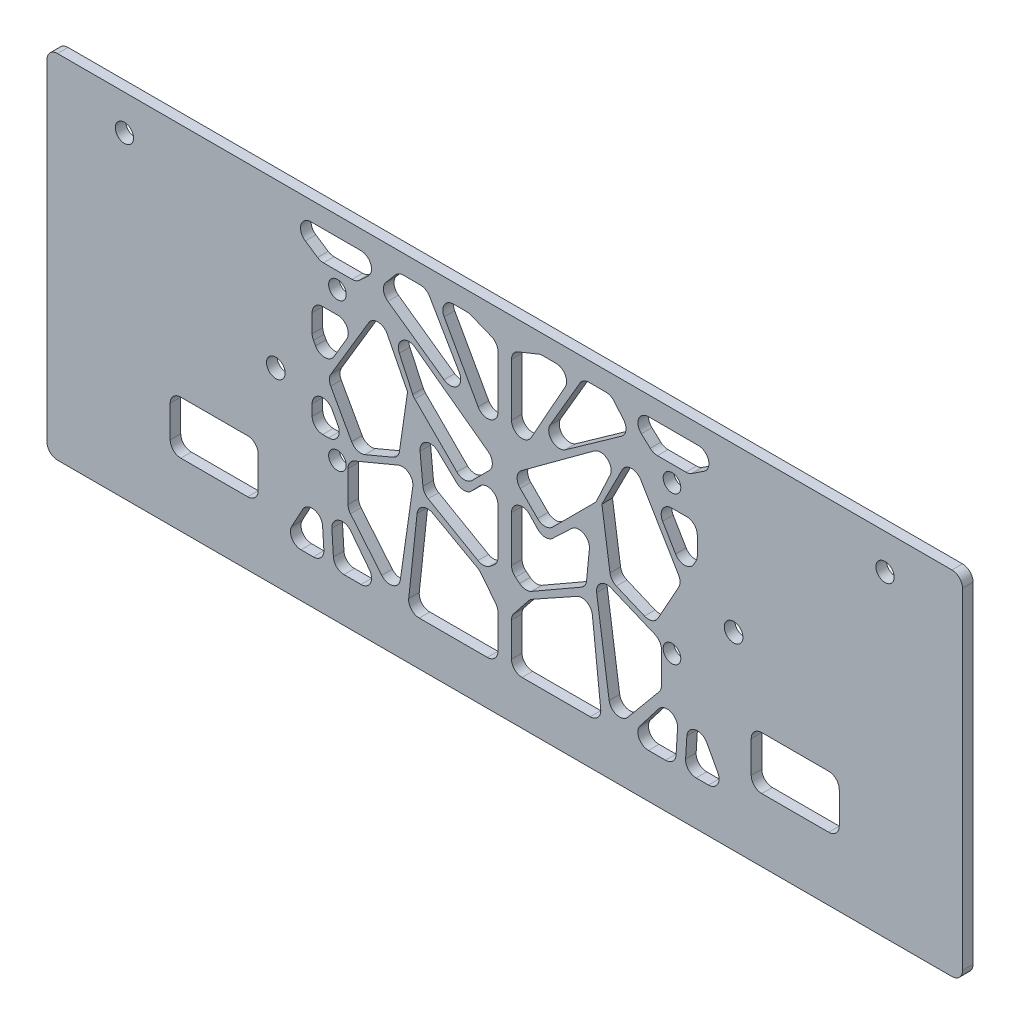
SolidWorks part; units mm, degrees
material "Thornel Mat VMA"
ref_plane "前视基准面" through (0, 0, 0) normal (0, 0, 1) x (1, 0, 0)
ref_plane "上视基准面" through (0, 0, 0) normal (0, 1, 0) x (1, 0, 0)
ref_plane "右视基准面" through (0, 0, 0) normal (1, 0, 0) x (0, 0, -1)
other "Configuration Table"
sketch "草图1" plane through (0, 0, 0) normal (0, 0, 1) x (1, 0, 0)
  line L1 (130, -50) -> (-130, -50)
  line L2 (130, -50) -> (130, 50)
  line L3 (130, 50) -> (-130, 50)
  line L4 (-130, -50) -> (-130, 50)
  line L5 (130, -50) -> (-130, 50) construction
  line L6 (130, 50) -> (-130, -50) construction
  point P0 (0, 0)
  dimension "D1" = 260
  dimension "D2" = 100
extrude "凸台-拉伸1" add sketch "草图1" along normal blind 3
fillet "圆角1" radius 3 4 edges at (130, 50, 1.5) (130, -50, 1.5) (-130, -50, 1.5) (-130, 50, 1.5)
sketch "草图3" plane through (0, 0, 0) normal (0, 0, -1) x (-1, 0, 0)
  line L0 (0, 50) -> (0, -50) construction
  line L1 (-127, 50) -> (127, 50) construction
  line L2 (127, -50) -> (-127, -50) construction
  line L3 (47.5, 50) -> (47.5, -50) construction
  line L5 (-47.5, 50) -> (-47.5, -50) construction
  line L6 (-130, -47) -> (-130, 47) construction
  circle A0 centre (47.5, 31.7) radius 2.5
  circle A1 centre (47.5, -10.3) radius 2.5
  circle A2 centre (-47.5, -10.3) radius 2.5
  circle A3 centre (-47.5, 31.7) radius 2.5
  circle A4 centre (-65, 3.7) radius 2.65
  circle A5 centre (65, 3.7) radius 2.65
  dimension "D1" = 5
  dimension "D3" = 42
  dimension "D4" = 18.3
  dimension "D5" = 5.3
  dimension "D6" = 46.3
  dimension "D7" = 65
  dimension "D2" = 47.5
extrude "切除-拉伸1" cut sketch "草图3" against normal blind 3
sketch "草图4" plane through (0, 0, 0) normal (0, 0, -1) x (-1, 0, 0)
  line L0 (-130, -17) -> (130, -17) construction
  line L1 (-130, -47) -> (-130, 47) construction
  line L2 (130, 47) -> (130, -47) construction
  line L3 (0, 50) -> (0, -50) construction
  line L4 (-127, 50) -> (127, 50) construction
  line L5 (127, -50) -> (-127, -50) construction
  line L6 (70, -17) -> (70, -32)
  line L7 (-95, -17) -> (-70, -17)
  line L8 (-95, -17) -> (-95, -32)
  line L9 (-95, -32) -> (-70, -32)
  line L10 (-70, -17) -> (-70, -32)
  line L11 (95, -32) -> (70, -32)
  line L12 (95, -17) -> (95, -32)
  line L13 (95, -17) -> (70, -17)
  dimension "D1" = 67
  dimension "D2" = 25
  dimension "D3" = 15
  dimension "D4" = 70
extrude "切除-拉伸2" cut sketch "草图4" against normal blind 3
fillet "圆角2" radius 3 8 edges at (-95, -17, 1.5) (-95, -32, 1.5) (-70, -32, 1.5) (-70, -17, 1.5) (70, -17, 1.5) (70, -32, 1.5) (95, -32, 1.5) (95, -17, 1.5)
sketch "草图5" plane through (0, 0, 0) normal (0, 0, -1) x (-1, 0, 0)
  line L0 (0, 50) -> (0, -50) construction
  line L1 (-127, 50) -> (127, 50) construction
  line L2 (127, -50) -> (-127, -50) construction
  line L3 (-130, -47) -> (-130, 47) construction
  circle A0 centre (-108, 40) radius 2.6
  circle A1 centre (108, 40) radius 2.6
  dimension "D1" = 5.2
  dimension "D2" = 22
  dimension "D3" = 10
extrude "切除-拉伸3" cut sketch "草图5" against normal blind 10
sketch "草图6" plane through (0, 0, 0) normal (0, 0, -1) x (-1, 0, 0)
  line L0 (-1.9245, 39.2502) -> (1.9245, 39.2502) construction
  line L1 (0, 39.2502) -> (0, -50.9783) construction
  line L2 (-1.9245, -24.8225) -> (1.9245, -24.8225) construction
  point P7 (0, -24.8225)
  line B0 (-38.4364, -32.6363) -> (-43.7127, -25.8023)
  line B1 (-45.6595, -37.4697) -> (-40.8111, -37.4697)
  line B2 (-49.0815, -27.8231) -> (-48.6537, -34.6571)
  line B3 (-51.3608, -34.2822) -> (-51.7232, -28.4933)
  line B4 (-57.8516, -37.4697) -> (-54.3549, -37.4697)
  line B5 (-57.3555, -27.2524) -> (-60.4897, -33.0413)
  line B6 (13.5751, 3.8156) -> (25.5304, 15.7709)
  line B7 (4.3957, 8.7524) -> (9.3325, 3.8156)
  line B8 (25.4376, 28.4877) -> (4.7415, 13.2919)
  line B9 (26.1292, 16.6269) -> (29.9332, 24.8041)
  line B10 (9.3893, 1.2104) -> (7.1012, 3.6228)
  line B11 (18.9944, 6.1855) -> (13.6305, 1.0981)
  line B12 (23.2357, -4.5515) -> (24.0446, 3.7166)
  line B13 (7.5961, -14.9727) -> (21.7421, -6.862)
  line B14 (3.0494, -13.7675) -> (4.2288, -14.7119)
  line B15 (1.9245, 1.5584) -> (1.9245, -11.4257)
  line B16 (27.2608, -34.1487) -> (24.886, -12.0769)
  line B17 (4.9245, -37.4697) -> (24.278, -37.4697)
  line B18 (1.9245, -24.8225) -> (1.9245, -34.4697)
  line B19 (6.876, -17.5858) -> (2.5828, -22.9473)
  line B20 (20.4438, -9.7768) -> (7.7583, -16.8399)
  line B21 (-1.9245, -34.4697) -> (-1.9245, -24.8225)
  line B22 (-24.278, -37.4697) -> (-4.9245, -37.4697)
  line B23 (-24.886, -12.0769) -> (-27.2608, -34.1487)
  line B24 (-7.7583, -16.8399) -> (-20.4438, -9.7768)
  line B25 (-2.5828, -22.9473) -> (-6.876, -17.5858)
  line B26 (-29.6511, -30.7817) -> (-26.1014, -6.0365)
  line B27 (-43.8095, -21.5832) -> (-34.9282, -32.2728)
  line B28 (-44.502, -10.805) -> (-44.502, -19.6661)
  line B29 (-30.2276, -2.8425) -> (-42.6586, -8.0369)
  line B30 (-13.6305, 1.0981) -> (-18.9944, 6.1855)
  line B31 (-7.1012, 3.6228) -> (-9.3893, 1.2104)
  line B32 (-1.9245, -11.4257) -> (-1.9245, 1.5584)
  line B33 (-4.2288, -14.7119) -> (-3.0494, -13.7675)
  line B34 (-21.7421, -6.862) -> (-7.5961, -14.9727)
  line B35 (-24.0446, 3.7166) -> (-23.2357, -4.5515)
  line B36 (-4.7415, 13.2919) -> (-25.4376, 28.4877)
  line B37 (-9.3325, 3.8156) -> (-4.3957, 8.7524)
  line B38 (-25.5304, 15.7709) -> (-13.5751, 3.8156)
  line B39 (-29.9332, 24.8041) -> (-26.1292, 16.6269)
  line B40 (-29.8981, 0.7081) -> (-27.5954, 16.4873)
  line B41 (-39.6959, -4.9911) -> (-31.702, -1.6233)
  line B42 (-49.4076, 6.9859) -> (-43.4834, -3.6828)
  line B43 (-38.62, 28.0131) -> (-49.3623, 9.9775)
  line B44 (-27.5954, 16.4873) -> (-33.3685, 27.8379)
  line B45 (-54.3064, 15.808) -> (-53.7196, 14.7513)
  line B46 (-54.6836, 22.4337) -> (-54.6836, 17.2643)
  line B47 (-47.4272, 25.4337) -> (-51.6836, 25.4337)
  line B48 (-48.5124, 14.6844) -> (-44.8427, 20.9104)
  line B49 (-40.8365, 44.6049) -> (-54.9861, 44.6049)
  line B50 (-41.3149, 37.0828) -> (-38.8028, 39.3995)
  line B51 (-51.4759, 36.2882) -> (-43.3487, 36.2882)
  line B52 (-56.6386, 39.101) -> (-53.1283, 36.7843)
  line B53 (-12.9018, 28.6255) -> (-21.3518, 43.1161)
  line B54 (-33.1725, 35.9785) -> (-17.2293, 24.6675)
  line B55 (-31.0413, 43.5411) -> (-33.7281, 40.3615)
  line B56 (-23.9433, 44.6049) -> (-28.7499, 44.6049)
  line B57 (-17.1953, 40.1446) -> (-7.5451, 22.8267)
  line B58 (-10.751, 44.6049) -> (-14.5747, 44.6049)
  line B59 (-3.8005, 42.0317) -> (-9.6269, 44.3863)
  line B60 (-1.9245, 24.287) -> (-1.9245, 39.2502)
  line B61 (9.6269, 44.3863) -> (3.8005, 42.0317)
  line B62 (14.5747, 44.6049) -> (10.751, 44.6049)
  line B63 (7.5451, 22.8267) -> (17.1953, 40.1446)
  line B64 (1.9245, 39.2502) -> (1.9245, 24.287)
  line B65 (17.2293, 24.6675) -> (33.1725, 35.9785)
  line B66 (21.3518, 43.1161) -> (12.9018, 28.6255)
  line B67 (28.7499, 44.6049) -> (23.9433, 44.6049)
  line B68 (33.7281, 40.3615) -> (31.0413, 43.5411)
  line B69 (43.3487, 36.2882) -> (51.4759, 36.2882)
  line B70 (38.8028, 39.3995) -> (41.3149, 37.0828)
  line B71 (54.9861, 44.6049) -> (40.8365, 44.6049)
  line B72 (53.1283, 36.7843) -> (56.6386, 39.101)
  line B73 (51.6836, 25.4337) -> (47.4272, 25.4337)
  line B74 (54.6836, 17.2643) -> (54.6836, 22.4337)
  line B75 (53.7196, 14.7513) -> (54.3064, 15.808)
  line B76 (44.8427, 20.9104) -> (48.5124, 14.6844)
  line B77 (49.0523, 1.4853) -> (47.3653, -1.5951)
  line B78 (54.6836, -3.0361) -> (54.6836, 0.0443)
  line B79 (49.9966, -6.0361) -> (51.6836, -6.0361)
  line B80 (43.4834, -3.6828) -> (49.4076, 6.9859)
  line B81 (31.702, -1.6233) -> (39.6959, -4.9911)
  line B82 (27.5954, 16.4873) -> (29.8981, 0.7081)
  line B83 (33.3685, 27.8379) -> (27.5954, 16.4873)
  line B84 (49.3623, 9.9775) -> (38.62, 28.0131)
  line B85 (60.4897, -33.0413) -> (57.3555, -27.2524)
  line B86 (54.3549, -37.4697) -> (57.8516, -37.4697)
  line B87 (51.7232, -28.4933) -> (51.3608, -34.2822)
  line B88 (48.6537, -34.6571) -> (49.0815, -27.8231)
  line B89 (40.8111, -37.4697) -> (45.6595, -37.4697)
  line B90 (43.7127, -25.8023) -> (38.4364, -32.6363)
  line B91 (44.502, -19.6661) -> (44.502, -10.805)
  line B92 (34.9282, -32.2728) -> (43.8095, -21.5832)
  line B93 (26.1014, -6.0365) -> (29.6511, -30.7817)
  line B94 (42.6586, -8.0369) -> (30.2276, -2.8425)
  arc B95 (-40.8111, -37.4697) -> (-38.4364, -32.6363) centre (-40.8111, -34.4697) ccw
  arc B96 (-48.6537, -34.6571) -> (-45.6595, -37.4697) centre (-45.6595, -34.4697) ccw
  arc B97 (-43.7127, -25.8023) -> (-49.0815, -27.8231) centre (-46.0874, -27.6356) ccw
  arc B98 (-54.3549, -37.4697) -> (-51.3608, -34.2822) centre (-54.3549, -34.4697) ccw
  arc B99 (-60.4897, -33.0413) -> (-57.8516, -37.4697) centre (-57.8516, -34.4697) ccw
  arc B100 (-51.7232, -28.4933) -> (-57.3555, -27.2524) centre (-54.7173, -28.6808) ccw
  arc B101 (9.3325, 3.8156) -> (13.5751, 3.8156) centre (11.4538, 5.937) ccw
  arc B102 (4.7415, 13.2919) -> (4.3957, 8.7524) centre (6.517, 10.8737) ccw
  arc B103 (29.9332, 24.8041) -> (25.4376, 28.4877) centre (27.2131, 26.0695) ccw
  arc B104 (25.5304, 15.7709) -> (26.1292, 16.6269) centre (23.4091, 17.8923) ccw
  arc B105 (9.3893, 1.2104) -> (13.6305, 1.0981) centre (11.566, 3.2748) ccw
  arc B106 (24.0446, 3.7166) -> (18.9944, 6.1855) centre (21.0588, 4.0088) ccw
  arc B107 (21.7421, -6.862) -> (23.2357, -4.5515) centre (20.2499, -4.2594) ccw
  arc B108 (4.2288, -14.7119) -> (7.5961, -14.9727) centre (6.1039, -12.3701) ccw
  arc B109 (1.9245, -11.4257) -> (3.0494, -13.7675) centre (4.9245, -11.4257) ccw
  arc B110 (7.1012, 3.6228) -> (1.9245, 1.5584) centre (4.9245, 1.5584) ccw
  arc B111 (24.278, -37.4697) -> (27.2608, -34.1487) centre (24.278, -34.4697) ccw
  arc B112 (1.9245, -34.4697) -> (4.9245, -37.4697) centre (4.9245, -34.4697) ccw
  arc B113 (2.5828, -22.9473) -> (1.9245, -24.8225) centre (4.9245, -24.8225) ccw
  arc B114 (7.7583, -16.8399) -> (6.876, -17.5858) centre (9.2177, -19.461) ccw
  arc B115 (24.886, -12.0769) -> (20.4438, -9.7768) centre (21.9032, -12.3979) ccw
  arc B116 (-4.9245, -37.4697) -> (-1.9245, -34.4697) centre (-4.9245, -34.4697) ccw
  arc B117 (-27.2608, -34.1487) -> (-24.278, -37.4697) centre (-24.278, -34.4697) ccw
  arc B118 (-20.4438, -9.7768) -> (-24.886, -12.0769) centre (-21.9032, -12.3979) ccw
  arc B119 (-6.876, -17.5858) -> (-7.7583, -16.8399) centre (-9.2177, -19.461) ccw
  arc B120 (-1.9245, -24.8225) -> (-2.5828, -22.9473) centre (-4.9245, -24.8225) ccw
  arc B121 (-34.9282, -32.2728) -> (-29.6511, -30.7817) centre (-32.6207, -30.3557) ccw
  arc B122 (-44.502, -19.6661) -> (-43.8095, -21.5832) centre (-41.502, -19.6661) ccw
  arc B123 (-42.6586, -8.0369) -> (-44.502, -10.805) centre (-41.502, -10.805) ccw
  arc B124 (-26.1014, -6.0365) -> (-30.2276, -2.8425) centre (-29.071, -5.6105) ccw
  arc B125 (-13.6305, 1.0981) -> (-9.3893, 1.2104) centre (-11.566, 3.2748) ccw
  arc B126 (-1.9245, 1.5584) -> (-7.1012, 3.6228) centre (-4.9245, 1.5584) ccw
  arc B127 (-3.0494, -13.7675) -> (-1.9245, -11.4257) centre (-4.9245, -11.4257) ccw
  arc B128 (-7.5961, -14.9727) -> (-4.2288, -14.7119) centre (-6.1039, -12.3701) ccw
  arc B129 (-23.2357, -4.5515) -> (-21.7421, -6.862) centre (-20.2499, -4.2594) ccw
  arc B130 (-18.9944, 6.1855) -> (-24.0446, 3.7166) centre (-21.0588, 4.0088) ccw
  arc B131 (-4.3957, 8.7524) -> (-4.7415, 13.2919) centre (-6.517, 10.8737) ccw
  arc B132 (-13.5751, 3.8156) -> (-9.3325, 3.8156) centre (-11.4538, 5.937) ccw
  arc B133 (-26.1292, 16.6269) -> (-25.5304, 15.7709) centre (-23.4091, 17.8923) ccw
  arc B134 (-25.4376, 28.4877) -> (-29.9332, 24.8041) centre (-27.2131, 26.0695) ccw
  arc B135 (-31.702, -1.6233) -> (-29.8981, 0.7081) centre (-32.8667, 1.1414) ccw
  arc B136 (-43.4834, -3.6828) -> (-39.6959, -4.9911) centre (-40.8606, -2.2264) ccw
  arc B137 (-49.3623, 9.9775) -> (-49.4076, 6.9859) centre (-46.7848, 8.4423) ccw
  arc B138 (-33.3685, 27.8379) -> (-38.62, 28.0131) centre (-36.0425, 26.4779) ccw
  arc B139 (-54.6836, 17.2643) -> (-54.3064, 15.808) centre (-51.6836, 17.2643) ccw
  arc B140 (-51.6836, 25.4337) -> (-54.6836, 22.4337) centre (-51.6836, 22.4337) ccw
  arc B141 (-44.8427, 20.9104) -> (-47.4272, 25.4337) centre (-47.4272, 22.4337) ccw
  arc B142 (-53.7196, 14.7513) -> (-48.5124, 14.6844) centre (-51.0968, 16.2077) ccw
  arc B143 (-38.8028, 39.3995) -> (-40.8365, 44.6049) centre (-40.8365, 41.6049) ccw
  arc B144 (-43.3487, 36.2882) -> (-41.3149, 37.0828) centre (-43.3487, 39.2882) ccw
  arc B145 (-53.1283, 36.7843) -> (-51.4759, 36.2882) centre (-51.4759, 39.2882) ccw
  arc B146 (-54.9861, 44.6049) -> (-56.6386, 39.101) centre (-54.9861, 41.6049) ccw
  arc B147 (-17.2293, 24.6675) -> (-12.9018, 28.6255) centre (-15.4934, 27.1143) ccw
  arc B148 (-33.7281, 40.3615) -> (-33.1725, 35.9785) centre (-31.4367, 38.4253) ccw
  arc B149 (-28.7499, 44.6049) -> (-31.0413, 43.5411) centre (-28.7499, 41.6049) ccw
  arc B150 (-21.3518, 43.1161) -> (-23.9433, 44.6049) centre (-23.9433, 41.6049) ccw
  arc B151 (-14.5747, 44.6049) -> (-17.1953, 40.1446) centre (-14.5747, 41.6049) ccw
  arc B152 (-9.6269, 44.3863) -> (-10.751, 44.6049) centre (-10.751, 41.6049) ccw
  arc B153 (-1.9245, 39.2502) -> (-3.8005, 42.0317) centre (-4.9245, 39.2502) ccw
  arc B154 (-7.5451, 22.8267) -> (-1.9245, 24.287) centre (-4.9245, 24.287) ccw
  arc B155 (10.751, 44.6049) -> (9.6269, 44.3863) centre (10.751, 41.6049) ccw
  arc B156 (17.1953, 40.1446) -> (14.5747, 44.6049) centre (14.5747, 41.6049) ccw
  arc B157 (1.9245, 24.287) -> (7.5451, 22.8267) centre (4.9245, 24.287) ccw
  arc B158 (3.8005, 42.0317) -> (1.9245, 39.2502) centre (4.9245, 39.2502) ccw
  arc B159 (12.9018, 28.6255) -> (17.2293, 24.6675) centre (15.4934, 27.1143) ccw
  arc B160 (23.9433, 44.6049) -> (21.3518, 43.1161) centre (23.9433, 41.6049) ccw
  arc B161 (31.0413, 43.5411) -> (28.7499, 44.6049) centre (28.7499, 41.6049) ccw
  arc B162 (33.1725, 35.9785) -> (33.7281, 40.3615) centre (31.4367, 38.4253) ccw
  arc B163 (41.3149, 37.0828) -> (43.3487, 36.2882) centre (43.3487, 39.2882) ccw
  arc B164 (40.8365, 44.6049) -> (38.8028, 39.3995) centre (40.8365, 41.6049) ccw
  arc B165 (56.6386, 39.101) -> (54.9861, 44.6049) centre (54.9861, 41.6049) ccw
  arc B166 (51.4759, 36.2882) -> (53.1283, 36.7843) centre (51.4759, 39.2882) ccw
  arc B167 (54.6836, 22.4337) -> (51.6836, 25.4337) centre (51.6836, 22.4337) ccw
  arc B168 (54.3064, 15.808) -> (54.6836, 17.2643) centre (51.6836, 17.2643) ccw
  arc B169 (48.5124, 14.6844) -> (53.7196, 14.7513) centre (51.0968, 16.2077) ccw
  arc B170 (47.4272, 25.4337) -> (44.8427, 20.9104) centre (47.4272, 22.4337) ccw
  arc B171 (54.6836, 0.0443) -> (49.0523, 1.4853) centre (51.6836, 0.0443) ccw
  arc B172 (51.6836, -6.0361) -> (54.6836, -3.0361) centre (51.6836, -3.0361) ccw
  arc B173 (47.3653, -1.5951) -> (49.9966, -6.0361) centre (49.9966, -3.0361) ccw
  arc B174 (39.6959, -4.9911) -> (43.4834, -3.6828) centre (40.8606, -2.2264) ccw
  arc B175 (29.8981, 0.7081) -> (31.702, -1.6233) centre (32.8667, 1.1414) ccw
  arc B176 (38.62, 28.0131) -> (33.3685, 27.8379) centre (36.0425, 26.4779) ccw
  arc B177 (49.4076, 6.9859) -> (49.3623, 9.9775) centre (46.7848, 8.4423) ccw
  arc B178 (57.8516, -37.4697) -> (60.4897, -33.0413) centre (57.8516, -34.4697) ccw
  arc B179 (51.3608, -34.2822) -> (54.3549, -37.4697) centre (54.3549, -34.4697) ccw
  arc B180 (57.3555, -27.2524) -> (51.7232, -28.4933) centre (54.7173, -28.6808) ccw
  arc B181 (45.6595, -37.4697) -> (48.6537, -34.6571) centre (45.6595, -34.4697) ccw
  arc B182 (38.4364, -32.6363) -> (40.8111, -37.4697) centre (40.8111, -34.4697) ccw
  arc B183 (49.0815, -27.8231) -> (43.7127, -25.8023) centre (46.0874, -27.6356) ccw
  arc B184 (43.8095, -21.5832) -> (44.502, -19.6661) centre (41.502, -19.6661) ccw
  arc B185 (29.6511, -30.7817) -> (34.9282, -32.2728) centre (32.6207, -30.3557) ccw
  arc B186 (30.2276, -2.8425) -> (26.1014, -6.0365) centre (29.071, -5.6105) ccw
  arc B187 (44.502, -10.805) -> (42.6586, -8.0369) centre (41.502, -10.805) ccw
sketch_block_instance "块1-1"
sketch_block "块1"
extrude "切除-拉伸4" cut sketch "草图6" against normal blind 10
sketch "草图7" plane through (0, 0, 3) normal (0, 0, 1) x (1, 0, 0)
  line L0 (-48.5945, 44.6049) -> (-154.2525, 44.6049) construction
  line L1 (-40.8365, 44.6049) -> (-54.9861, 44.6049) construction
